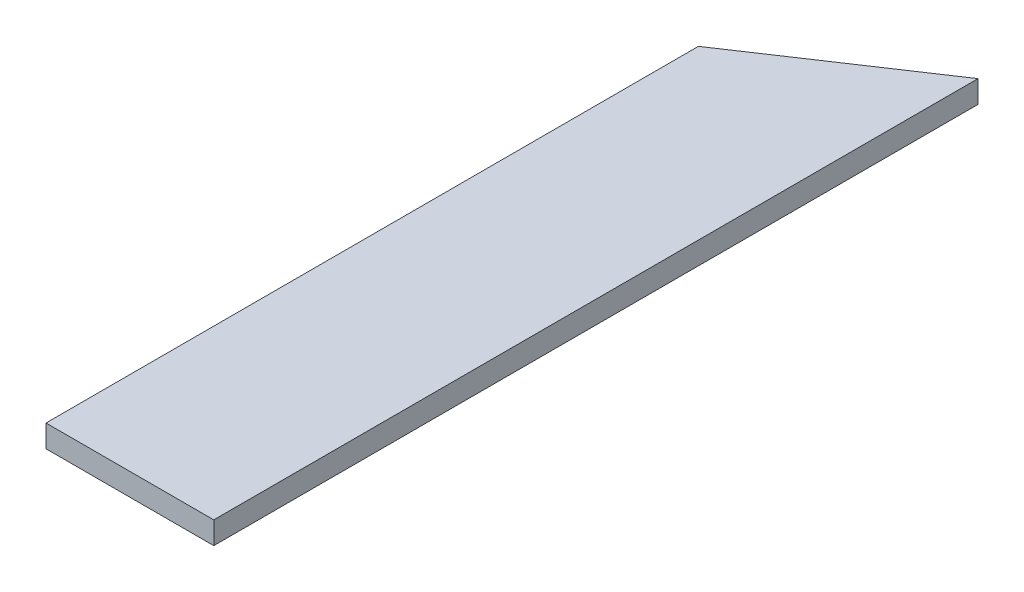
SolidWorks part; units mm, degrees
ref_plane "Front Plane" through (0, 0, 0) normal (0, 0, 1) x (1, 0, 0)
ref_plane "Top Plane" through (0, 0, 0) normal (0, 1, 0) x (1, 0, 0)
ref_plane "Right Plane" through (0, 0, 0) normal (1, 0, 0) x (0, 0, -1)
sketch "Sketch1" plane through (0, 0, 0) normal (0, 1, 0) x (1, 0, 0)
  line L0 (22.86, 88.9) -> (22.86, 104.14)
  line L1 (0, 0) -> (22.86, 0)
  line L2 (0, 0) -> (0, 88.9)
  line L3 (0, 88.9) -> (22.86, 88.9)
  line L4 (22.86, 0) -> (22.86, 88.9)
  line L5 (0, 88.9) -> (22.86, 104.14)
  line L6 (22.86, 104.14) -> (0, 88.9)
  line L7 (0, 0) -> (22.86, 0)
  dimension "D1" = 88.9
  dimension "D2" = 22.86
  dimension "D3" = 15.24
extrude "Boss-Extrude1" add sketch "Sketch1" along normal blind 4.318 contours L5 L3 L0 | L1 L4 L3 L2
sketch "Sketch2" plane through (0, 4.318, 0) normal (0, 1, 0) x (1, 0, 0)
  line L1 (-11.8324, 156.5351) -> (48.9177, 156.5351)
  line L2 (-11.8324, 156.5351) -> (-11.8324, -34.7896)
  line L3 (-11.8324, -34.7896) -> (48.9177, -34.7896)
  line L4 (48.9177, 156.5351) -> (48.9177, -34.7896)
extrude "Cut-Extrude1" cut sketch "Sketch2" against normal blind 1.27
